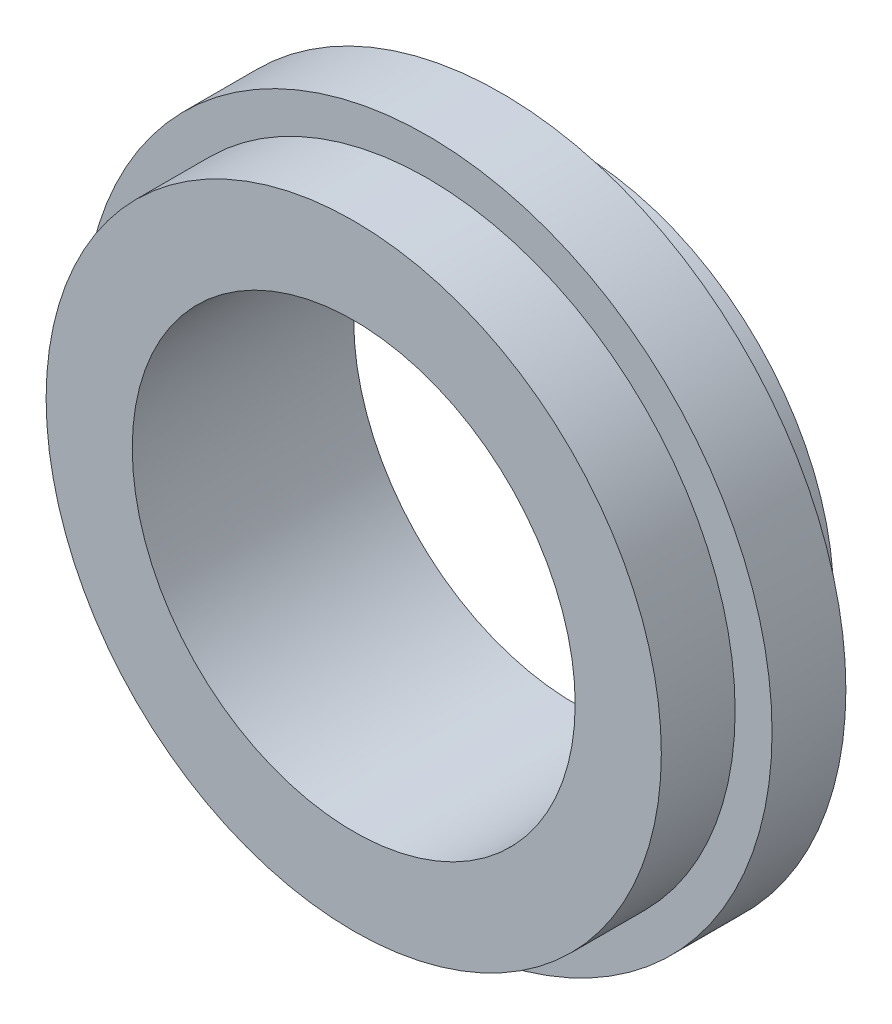
SolidWorks part; units mm, degrees
material "6061 合金"
ref_plane "前视基准面" through (0, 0, 0) normal (0, 0, 1) x (1, 0, 0)
ref_plane "上视基准面" through (0, 0, 0) normal (0, 1, 0) x (1, 0, 0)
ref_plane "右视基准面" through (0, 0, 0) normal (1, 0, 0) x (0, 0, -1)
sketch "草图1" plane through (0, 0, 0) normal (0, 0, 1) x (1, 0, 0)
  circle A0 centre (0, 0) radius 9
  circle A1 centre (0, 0) radius 10.5
  dimension "D1" = 21
  dimension "D2" = 18
extrude "凸台-拉伸1" add sketch "草图1" along normal blind 3
sketch "草图2" plane through (0, 0, 3) normal (0, 0, 1) x (1, 0, 0)
  circle A0 centre (0, 0) radius 9
  circle A1 centre (0, 0) radius 14
  dimension "D1" = 28
  dimension "D2" = 18
extrude "凸台-拉伸2" add sketch "草图2" along normal blind 3
sketch "草图3" plane through (0, 0, 6) normal (0, 0, 1) x (1, 0, 0)
  circle A0 centre (0, 0) radius 9
  circle A1 centre (0, 0) radius 12.5
  dimension "D1" = 25
  dimension "D2" = 18
extrude "凸台-拉伸3" add sketch "草图3" along normal blind 3
